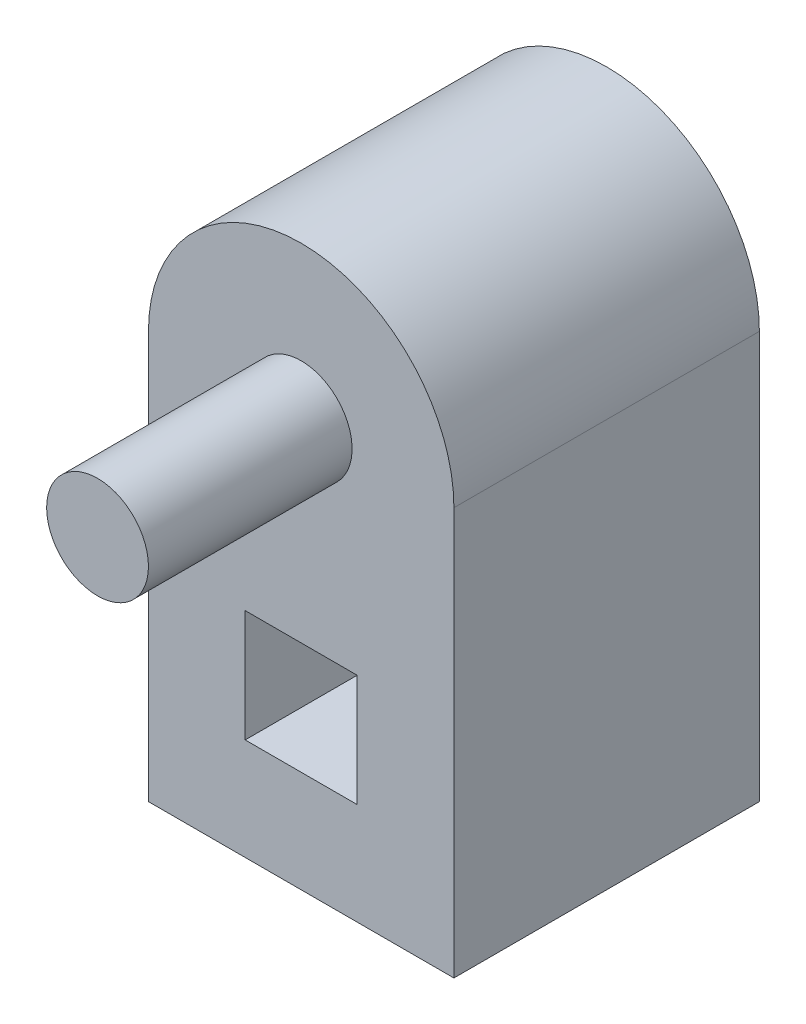
SolidWorks part; units mm, degrees
ref_plane "Front Plane" through (0, 0, 0) normal (0, 0, 1) x (1, 0, 0)
ref_plane "Top Plane" through (0, 0, 0) normal (0, 1, 0) x (1, 0, 0)
ref_plane "Right Plane" through (0, 0, 0) normal (1, 0, 0) x (0, 0, -1)
sketch "Sketch1" plane through (0, 0, 0) normal (0, 1, 0) x (1, 0, 0)
  line L1 (-38.1, 38.1) -> (38.1, 38.1)
  line L2 (-38.1, 38.1) -> (-38.1, -38.1)
  line L3 (-38.1, -38.1) -> (38.1, -38.1)
  line L4 (38.1, 38.1) -> (38.1, -38.1)
  line L5 (-38.1, 38.1) -> (38.1, -38.1) construction
  line L6 (-38.1, -38.1) -> (38.1, 38.1) construction
  point P0 (0, 0)
extrude "Boss-Extrude1" add sketch "Sketch1" along normal blind 101.6
sketch "Sketch2" plane through (0, 0, 0) normal (0, 0, 1) x (1, 0, 0)
  line L0 (-38.1, 101.6) -> (38.1, 101.6) construction
  circle A0 centre (0, 101.6) radius 38.1
extrude "Boss-Extrude2" add sketch "Sketch2" along normal through all and the other way through all
sketch "Sketch3" plane through (0, 0, 0) normal (0, 0, 1) x (1, 0, 0)
  line L0 (0, -41.91) -> (0, 41.91) construction
  line L1 (-13.97, 53.34) -> (13.97, 53.34)
  line L2 (-13.97, 53.34) -> (-13.97, 25.4)
  line L3 (-13.97, 25.4) -> (13.97, 25.4)
  line L4 (13.97, 53.34) -> (13.97, 25.4)
  line L5 (-13.97, 53.34) -> (13.97, 25.4) construction
  line L6 (-13.97, 25.4) -> (13.97, 53.34) construction
  line L8 (41.91, 0) -> (-41.91, 0) construction
  point P0 (0, 39.37)
  dimension "D1" = 25.4
extrude "Cut-Extrude1" cut sketch "Sketch3" against normal through all both and the other way through all
sketch "Sketch4" plane through (0, 0, 0) normal (0, 0, 1) x (1, 0, 0)
  circle A0 centre (0, 101.6) radius 12.7
  dimension "D1" = 25.4
extrude "Boss-Extrude3" add sketch "Sketch4" along normal blind 88.9
